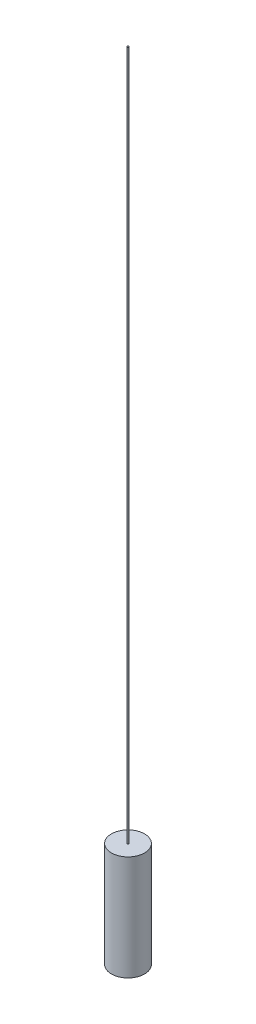
SolidWorks part; units mm, degrees
ref_plane "Front Plane" through (0, 0, 0) normal (0, 0, 1) x (1, 0, 0)
ref_plane "Top Plane" through (0, 0, 0) normal (0, 1, 0) x (1, 0, 0)
ref_plane "Right Plane" through (0, 0, 0) normal (1, 0, 0) x (0, 0, -1)
sketch "Sketch1" plane through (0, 0, 0) normal (0, 1, 0) x (1, 0, 0)
  circle A0 centre (0, 0) radius 6
  dimension "D1" = 12
extrude "Boss-Extrude1" add sketch "Sketch1" along normal blind 38
sketch "Sketch2" plane through (0, 38, 0) normal (0, 1, 0) x (1, 0, 0)
  circle A0 centre (0, 0) radius 0.3025
extrude "Boss-Extrude2" add sketch "Sketch2" along normal blind 250
